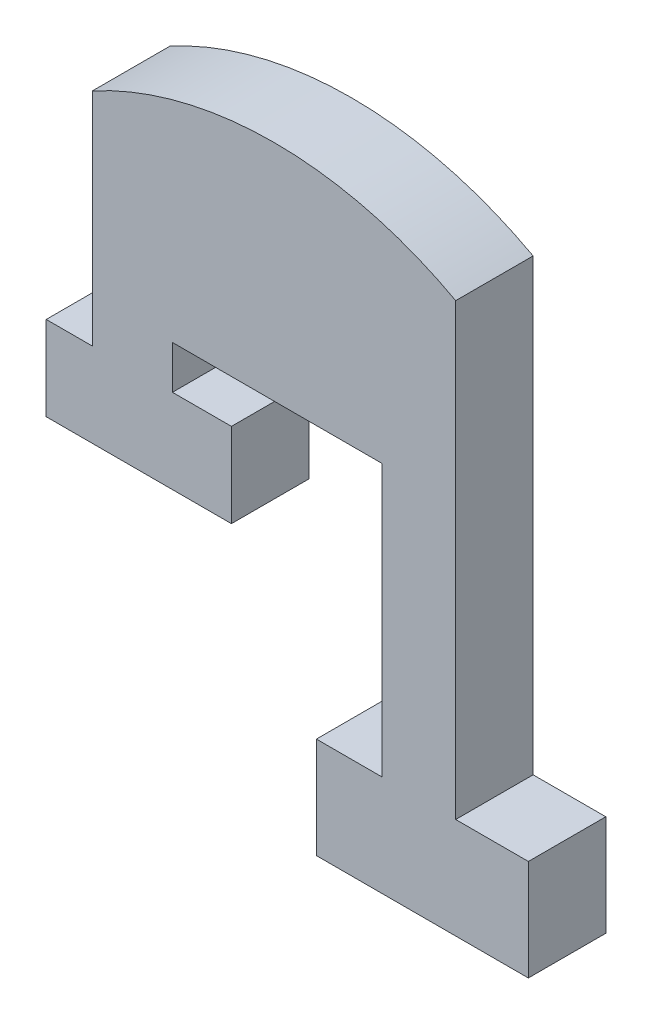
SolidWorks part; units mm, degrees
ref_plane "Front Plane" through (0, 0, 0) normal (0, 0, 1) x (1, 0, 0)
ref_plane "Top Plane" through (0, 0, 0) normal (0, 1, 0) x (1, 0, 0)
ref_plane "Right Plane" through (0, 0, 0) normal (1, 0, 0) x (0, 0, -1)
sketch "Sketch1" plane through (0, 0, 0) normal (0, 0, 1) x (1, 0, 0)
  line L0 (-57.8583, 0) -> (-57.8583, 45.9362)
  line L2 (35.9827, 45.9362) -> (35.9827, -85.9663)
  line L3 (35.9827, -85.9663) -> (16.952, -85.9663)
  line L4 (16.952, -85.9663) -> (16.952, 0)
  line L5 (16.952, 0) -> (-37.187, 0)
  line L6 (-37.187, 0) -> (-37.187, -22.64)
  line L7 (-37.187, -22.64) -> (-57.8583, -22.64)
  line L8 (-57.8583, -22.64) -> (-57.8583, 0)
  arc A0 (15.4581, 57.1959) -> (16.4851, 56.7457) centre (-34.5868, -58.3644) cw
  arc A1 (-57.8583, 45.9362) -> (35.9827, 45.9362) centre (-10.9378, -40.3636) cw
sketch "Sketch3" plane through (0, 0, 0) normal (0, 0, 1) x (1, 0, 0)
  line L1 (-69.7905, -11.1555) -> (-21.9489, -11.1555)
  line L2 (-69.7905, -11.1555) -> (-69.7905, -32.9247)
  line L3 (-69.7905, -32.9247) -> (-21.9489, -32.9247)
  line L4 (-21.9489, -11.1555) -> (-21.9489, -32.9247)
  line L5 (0, -70.1348) -> (54.7495, -70.1348)
  line L6 (0, -70.1348) -> (0, -96.2072)
  line L7 (0, -96.2072) -> (54.7495, -96.2072)
  line L8 (54.7495, -70.1348) -> (54.7495, -96.2072)
extrude "Boss-Extrude1" add sketch "Sketch1" along normal blind 20 contours A1 L0 L8 L7 L6 L5 L4 L3 L2
extrude "Boss-Extrude2" add sketch "Sketch3" along normal blind 20
